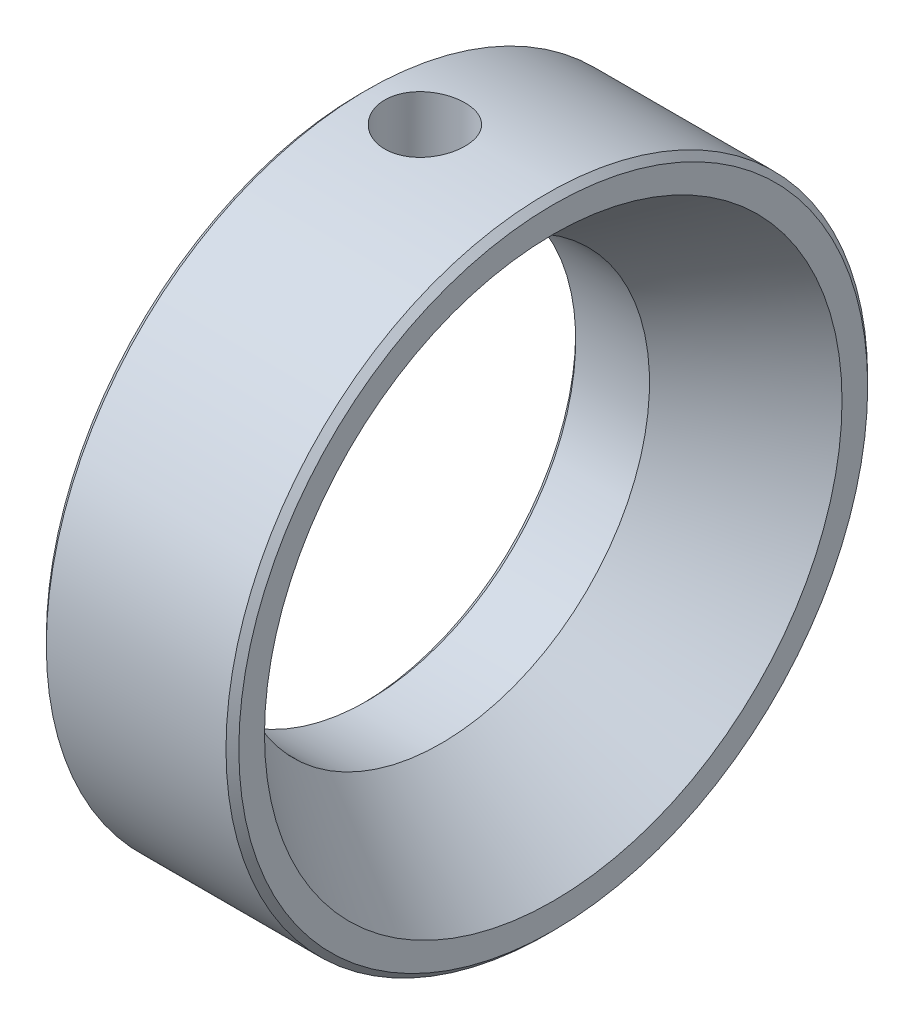
SolidWorks part; units mm, degrees
ref_plane "Спереди" through (0, 0, 0) normal (0, 0, 1) x (1, 0, 0)
ref_plane "Сверху" through (0, 0, 0) normal (0, 1, 0) x (1, 0, 0)
ref_plane "Справа" through (0, 0, 0) normal (1, 0, 0) x (0, 0, -1)
sketch "Эскиз1" plane through (0, 0, 0) normal (0, 0, 1) x (1, 0, 0)
  line L0 (-193.5366, 0) -> (200.8537, 0) construction
  line L1 (-37.6829, -65) -> (-37.6829, -100)
  line L2 (-37.6829, -100) -> (22.3171, -100)
  line L5 (-12.6829, -65) -> (-37.6829, -65)
  line L12 (-12.6829, -65) -> (22.3171, -90)
  line L13 (22.3171, -90) -> (22.3171, -100)
  dimension "D1" = 60
  dimension "D2" = 200
  dimension "D3" = 130
  dimension "D4" = 25
  dimension "D5" = 10
revolve "Повернуть1" add sketch "Эскиз1" angle 360 about L0
chamfer "Фаска1" distance 2 angle 45 3 edges at (-37.6829, 0, 65) (-37.6829, 0, 100) (22.3171, 0, 100)
sketch "Эскиз2" plane through (0, 0, 0) normal (0, 0, 1) x (1, 0, 0)
  line L0 (-17.6829, 126.6809) -> (-17.6829, -139.4708) construction
  line L2 (20.3171, -99.9023) -> (-50.3952, -99.9023) construction
  line L3 (20.3171, -100) -> (20.3171, 100) construction
  line L5 (-5.1829, -99.9023) -> (-5.1829, -79.9023)
  line L6 (-5.1829, -79.9023) -> (-17.6829, -79.9023)
  line L7 (-17.6829, -79.9023) -> (-17.6829, -99.9023)
  line L8 (20.3171, 100) -> (-53.5333, 100) construction
  line L9 (-17.6829, 100) -> (-5.1829, 100)
  line L10 (-5.1829, 100) -> (-5.1829, 80)
  line L11 (-5.1829, 80) -> (-17.6829, 80)
  line L12 (-17.6829, 80) -> (-17.6829, 100)
  line L13 (-5.1829, -99.9023) -> (-5.1829, -106.1321)
  line L14 (-5.1829, -106.1321) -> (-17.6829, -106.1321)
  line L15 (-17.6829, -106.1321) -> (-17.6829, -99.9023)
  dimension "D3" = 25
  dimension "D4" = 25
  dimension "D5" = 20
revolve "Вырез-Повернуть1" cut sketch "Эскиз2" angle 360 about L0
